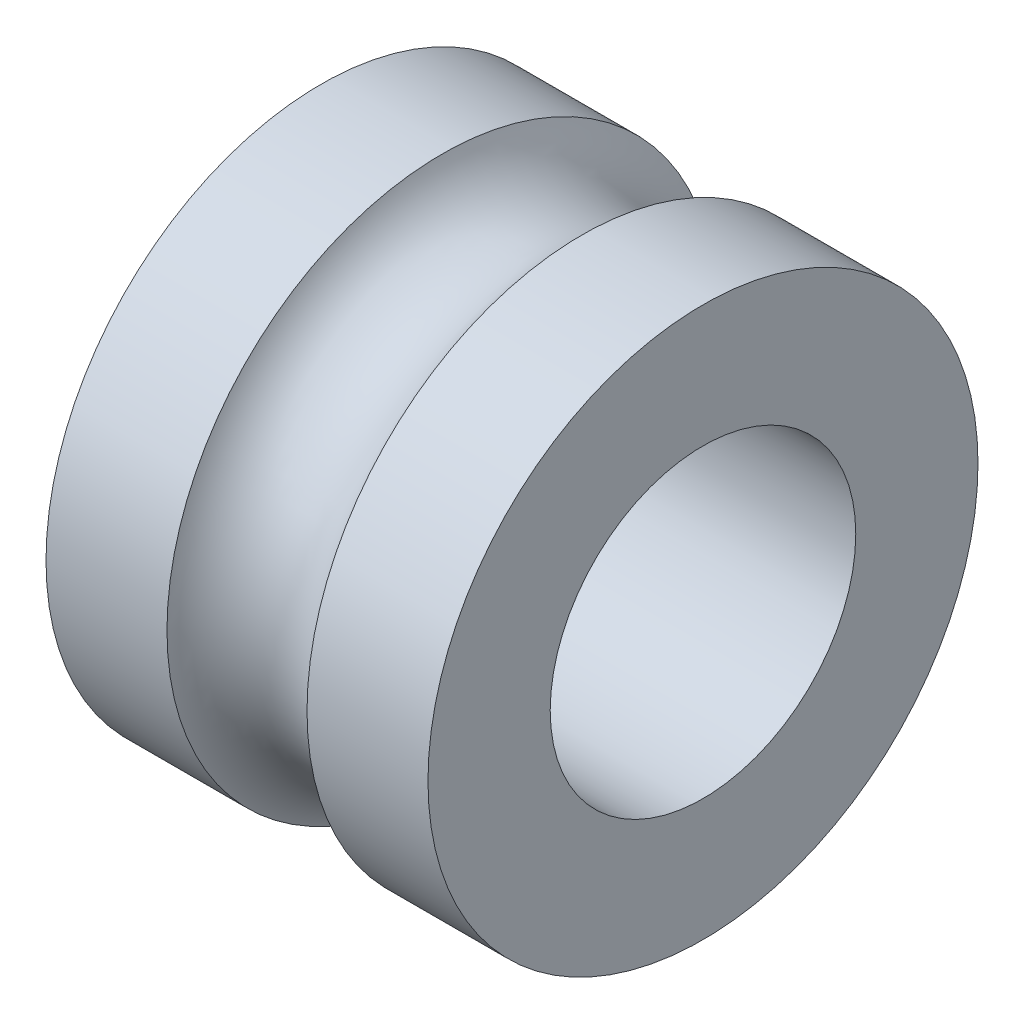
SolidWorks part; units mm, degrees
ref_plane "Plan de face" through (0, 0, 0) normal (0, 0, 1) x (1, 0, 0)
ref_plane "Plan de dessus" through (0, 0, 0) normal (0, 1, 0) x (1, 0, 0)
ref_plane "Plan de droite" through (0, 0, 0) normal (1, 0, 0) x (0, 0, -1)
sketch "Esquisse1" plane through (0, 0, 0) normal (0, 0, 1) x (1, 0, 0)
  line L0 (-36.4355, 0) -> (43.6569, 0) construction
  line L1 (0, -16.8069) -> (0, -26.8069) construction
  line L7 (4.5826, 18) -> (12.5, 18)
  line L8 (-12.5, 18) -> (-4.5826, 18)
  line L9 (-12.5, 18) -> (-12.5, 10)
  line L10 (-12.5, 10) -> (12.5, 10)
  line L11 (12.5, 18) -> (12.5, 10)
  arc A1 (-4.5826, 18) -> (4.5826, 18) centre (0, 20) ccw
  dimension "D5" = 10
  dimension "D4" = 5
  dimension "D2" = 25
  dimension "D3" = 8
  dimension "D7" = 12.5
revolve "Révolution2" add sketch "Esquisse1" angle 360 about L0
